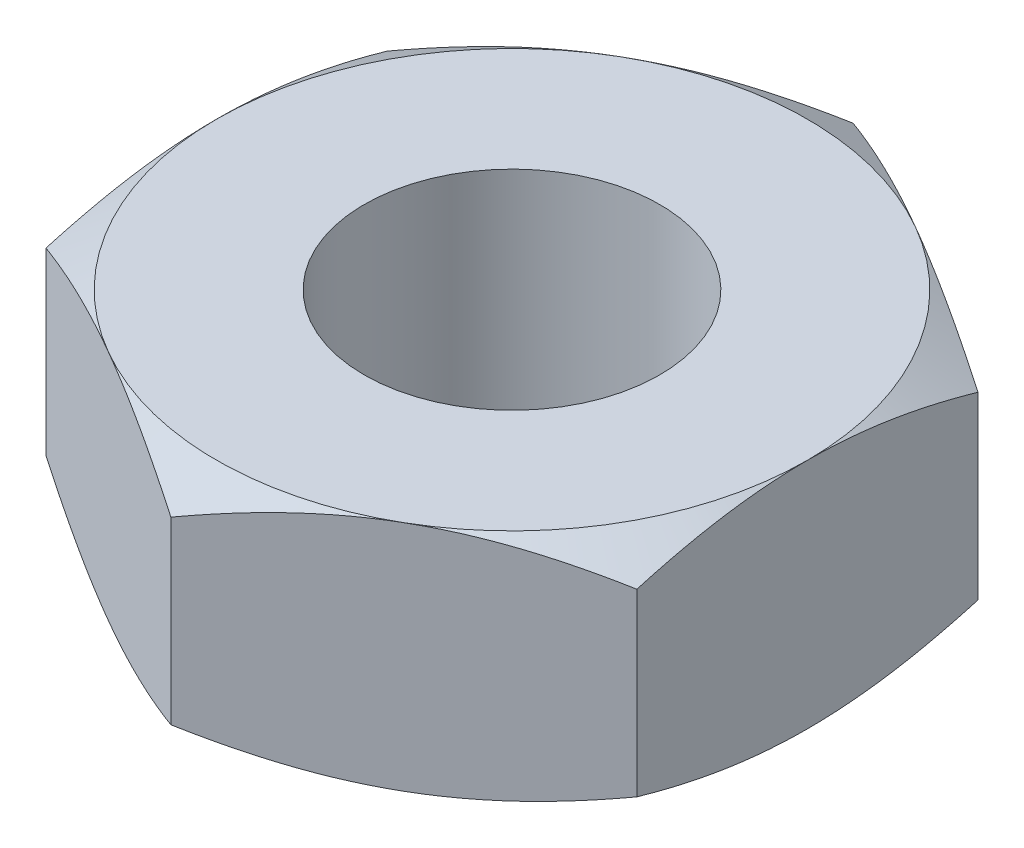
SolidWorks part; units mm, degrees
ref_plane "Front Plane" through (0, 0, 0) normal (0, 0, 1) x (1, 0, 0)
ref_plane "Top Plane" through (0, 0, 0) normal (0, 1, 0) x (1, 0, 0)
ref_plane "Right Plane" through (0, 0, 0) normal (1, 0, 0) x (0, 0, -1)
sketch "Sketch1" plane through (0, 0, 0) normal (0, 1, 0) x (1, 0, 0)
  line L1 (-13.7886, 7.3323) -> (-13.7886, -7.3323)
  line L2 (-13.7886, -7.3323) -> (-1.0886, -14.6647)
  line L3 (-1.0886, -14.6647) -> (11.6114, -7.3323)
  line L4 (11.6114, -7.3323) -> (11.6114, 7.3323)
  line L5 (11.6114, 7.3323) -> (-1.0886, 14.6647)
  line L6 (-1.0886, 14.6647) -> (-13.7886, 7.3323)
  circle A0 centre (-1.0886, 0) radius 12.7 construction
  dimension "D1" = 25.4
extrude "Boss-Extrude1" add sketch "Sketch1" along normal mid plane 10
sketch "Sketch2" plane through (0, 5, 0) normal (0, 1, 0) x (1, 0, 0)
  line L0 (-1.0886, 14.6647) -> (-1.0886, -14.6647) construction
  circle A0 centre (-1.0886, 0) radius 6.35
  dimension "D1" = 12.7
extrude "Cut-Extrude1" cut sketch "Sketch2" against normal through all
cosmetic thread "Cosmetic Thread1" parameters "D2"=14.2875
sketch "Sketch3" plane through (0, 5, 0) normal (0, 1, 0) x (1, 0, 0)
  circle A0 centre (-1.0886, 0) radius 12.7
extrude "Cut-Extrude2" cut sketch "Sketch3" against normal through all draft 60 flip side to cut
mirror "Mirror1" about plane through (0, 0, 0) normal (0, 1, 0) of "Cut-Extrude2"
